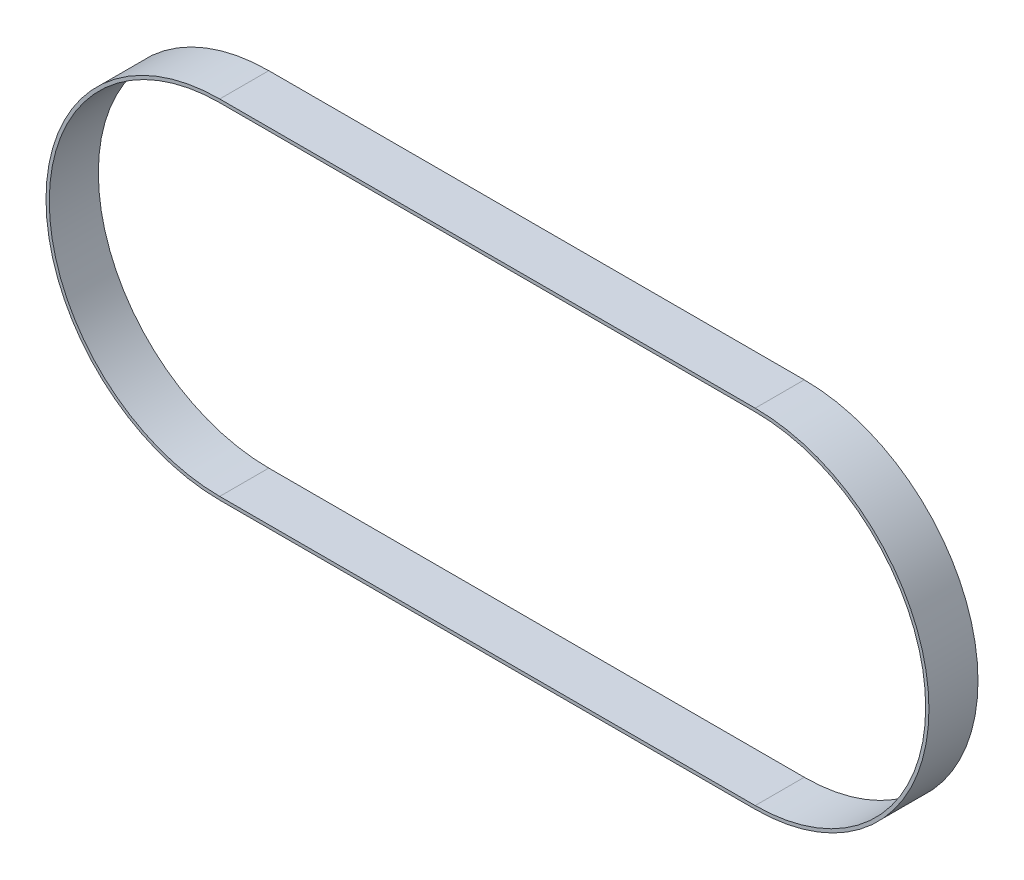
SolidWorks part; units mm, degrees
material "Rubber"
ref_plane "Front Plane" through (0, 0, 0) normal (0, 0, 1) x (1, 0, 0)
ref_plane "Top Plane" through (0, 0, 0) normal (0, 1, 0) x (1, 0, 0)
ref_plane "Right Plane" through (0, 0, 0) normal (1, 0, 0) x (0, 0, -1)
sketch "Sketch1" plane through (0, 0, 0) normal (0, 0, 1) x (1, 0, 0)
  line L0 (-81.875, 0) -> (81.875, 0) construction
  line L1 (-81.875, 52.1232) -> (81.875, 52.1232)
  line L2 (-81.875, -52.1232) -> (81.875, -52.1232)
  line L3 (-81.875, 53.1232) -> (81.875, 53.1232)
  line L4 (-81.875, -53.1232) -> (81.875, -53.1232)
  arc A0 (-81.875, 52.1232) -> (-81.875, -52.1232) centre (-81.875, 0) ccw
  arc A1 (81.875, -52.1232) -> (81.875, 52.1232) centre (81.875, 0) ccw
  arc A2 (81.875, -53.1232) -> (81.875, 53.1232) centre (81.875, 0) ccw
  arc A3 (-81.875, 53.1232) -> (-81.875, -53.1232) centre (-81.875, 0) ccw
  point P2 (0, 0)
  dimension "D1" = 163.75
  dimension "D2" = 52.1232
  dimension "D3" = 1
extrude "Boss-Extrude1" add sketch "Sketch1" along normal blind 15 contours A0 L2 A1 L1
